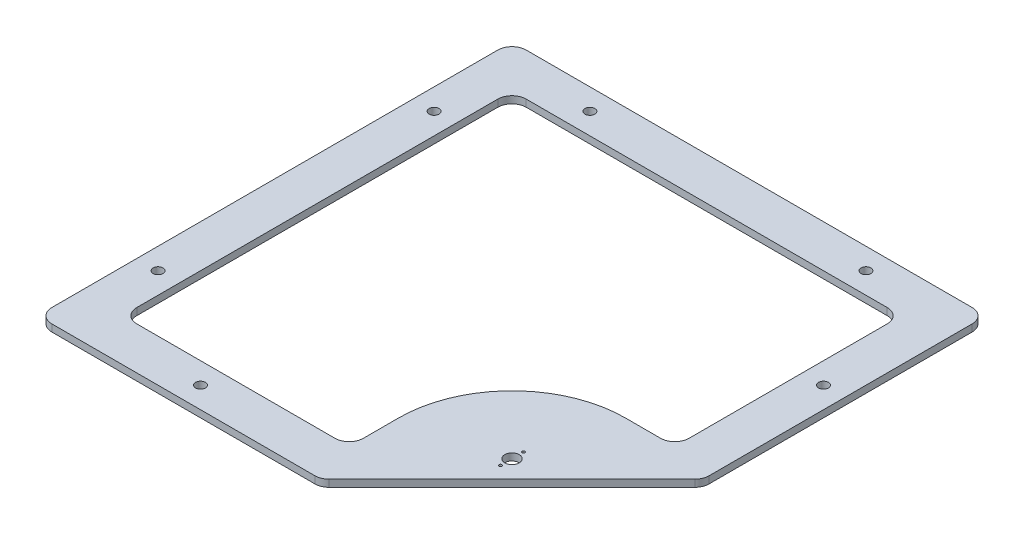
SolidWorks part; units mm, degrees
material "Acrylic (Medium-high impact)"
ref_plane "Front Plane" through (0, 0, 0) normal (0, 0, 1) x (1, 0, 0)
ref_plane "Top Plane" through (0, 0, 0) normal (0, 1, 0) x (1, 0, 0)
ref_plane "Right Plane" through (0, 0, 0) normal (1, 0, 0) x (0, 0, -1)
sketch "Sketch1" plane through (0, 0, 0) normal (0, 1, 0) x (1, 0, 0)
  line L1 (-212.725, -212.725) -> (212.725, -212.725)
  line L2 (-212.725, -212.725) -> (-212.725, 212.725)
  line L3 (-212.725, 212.725) -> (212.725, 212.725)
  line L4 (212.725, -212.725) -> (212.725, 212.725)
  line L5 (-212.725, -212.725) -> (212.725, 212.725) construction
  line L6 (-212.725, 212.725) -> (212.725, -212.725) construction
  point P0 (0, 0)
  dimension "D1" = 425.45
extrude "Boss-Extrude1" add sketch "Sketch1" along normal mid plane 6.35
sketch "Sketch2" plane through (0, 3.175, 0) normal (0, 1, 0) x (1, 0, 0)
  line L0 (212.725, -212.725) -> (212.725, -41.275)
  line L1 (212.725, -212.725) -> (212.725, 212.725) construction
  line L2 (212.725, -41.275) -> (41.275, -212.725)
  line L3 (-212.725, -212.725) -> (212.725, -212.725) construction
  line L4 (41.275, -212.725) -> (212.725, -212.725)
  dimension "D1" = 254
extrude "Cut-Extrude1" cut sketch "Sketch2" against normal through all
sketch "Sketch3" plane through (0, 3.175, 0) normal (0, 1, 0) x (1, 0, 0)
  line L0 (-212.725, -212.725) -> (41.275, -212.725) construction
  line L1 (212.725, -41.275) -> (212.725, 212.725) construction
  line L2 (111.125, -100.7999) -> (111.125, -121.4501) construction
  line L3 (-212.725, -212.725) -> (41.275, -212.725) construction
  line L4 (111.125, -111.125) -> (212.725, -111.125) construction
  line L5 (111.125, -111.125) -> (111.125, -212.725) construction
  line L6 (111.125, -212.725) -> (212.725, -212.725) construction
  line L7 (212.725, -111.125) -> (212.725, -212.725) construction
  circle A0 centre (111.125, -111.125) radius 6.477
  circle A1 centre (111.125, -100.7999) radius 1.27
  circle A2 centre (111.125, -121.4501) radius 1.27
  point P10 (111.125, -111.125)
  dimension "D1" = 12.954
  dimension "D4" = 2.54
  dimension "D2" = 101.6
  dimension "D3" = 101.6
  dimension "D5" = 10.3251
extrude "Cut-Extrude2" cut sketch "Sketch3" against normal through all
hole_wizard " (0.332) Diameter Hole1" positions "Sketch4" profile "Sketch5" hole size "S" standard "ANSI Inch" end condition through all
sketch "Sketch4" plane through (0, 3.175, 0) normal (0, 1, 0) x (1, 0, 0)
  line L1 (-193.675, -193.675) -> (193.675, -193.675) construction
  line L2 (-193.675, -193.675) -> (-193.675, 193.675) construction
  line L3 (-193.675, 193.675) -> (193.675, 193.675) construction
  line L4 (193.675, -193.675) -> (193.675, 193.675) construction
  line L7 (212.725, 212.725) -> (-212.725, 212.725) construction
  line L8 (-212.725, 212.725) -> (-212.725, -212.725) construction
  line L9 (-212.725, -212.725) -> (41.275, -212.725) construction
  line L10 (212.725, -41.275) -> (212.725, 212.725) construction
  point P0 (-85.725, -193.675)
  point P2 (-193.675, -123.825)
  point P4 (-193.675, 123.825)
  point P6 (-123.825, 193.675)
  point P8 (123.825, 193.675)
  point P10 (193.675, 85.725)
  dimension "D1" = 19.05
  dimension "D2" = 19.05
  dimension "D3" = 19.05
  dimension "D4" = 88.9
  dimension "D5" = 88.9
  dimension "D6" = 88.9
  dimension "D7" = 127
  dimension "D8" = 88.9
  dimension "D9" = 127
sketch "Sketch5" plane through (-85.725, 3.175, 193.675) normal (1, 0, 0) x (0, 0, 1)
  line L0 (0, 0) -> (0, 6.35)
  line L1 (0, 6.35) -> (4.4196, 6.35)
  line L2 (4.4196, 6.35) -> (4.4196, 0)
  line L5 (4.4196, 0) -> (0, 0)
  line L11 (0, -6.35) -> (0, 107.95) construction
  dimension "Thru Hole Dia." = 8.8392
  dimension "Thru Hole Depth" = 6.35
sketch "Sketch6" plane through (0, 3.175, 0) normal (0, 1, 0) x (1, 0, 0)
  line L0 (174.625, 174.625) -> (174.625, -28.575)
  line L1 (174.625, -28.575) -> (28.575, -28.575)
  line L2 (-174.625, -174.625) -> (-174.625, 174.625)
  line L3 (-174.625, 174.625) -> (174.625, 174.625)
  line L4 (28.575, -28.575) -> (28.575, -174.625)
  line L5 (28.575, -174.625) -> (-174.625, -174.625)
  line L6 (212.725, 212.725) -> (-212.725, 212.725) construction
  line L7 (-212.725, 212.725) -> (-212.725, -212.725) construction
  line L8 (-212.725, -212.725) -> (41.275, -212.725) construction
  line L9 (212.725, -41.275) -> (212.725, 212.725) construction
  point P0 (0, 0)
  dimension "D1" = 38.1
  dimension "D2" = 38.1
  dimension "D3" = 38.1
  dimension "D4" = 38.1
  dimension "D5" = 203.2
extrude "Cut-Extrude3" cut sketch "Sketch6" against normal through all
fillet "Fillet1" radius 12.7 10 edges at (-174.625, 0, -174.625) (-212.725, 0, -212.725) (174.625, 0, -174.625) (212.725, 0, -212.725) (174.625, 0, 28.575) (212.725, 0, 41.275) (41.275, 0, 212.725) (28.575, 0, 174.625) (-174.625, 0, 174.625) (-212.725, 0, 212.725)
fillet "Fillet2" radius 101.6 1 edges at (28.575, 0, 28.575)
